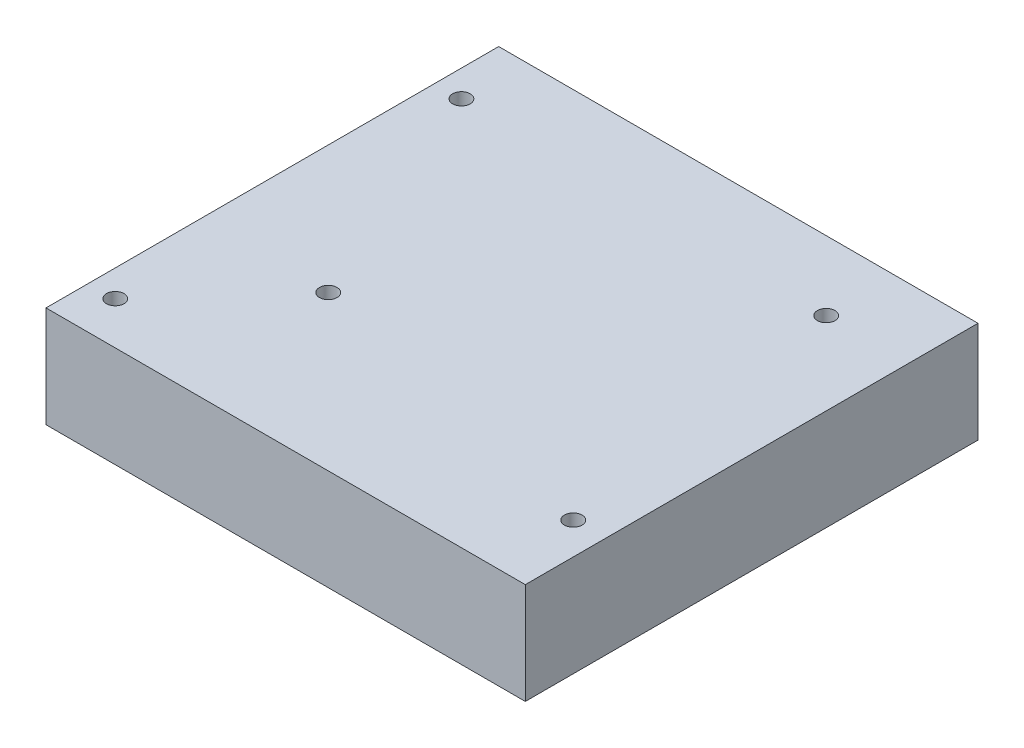
SolidWorks part; units mm, degrees
ref_plane "Front Plane" through (0, 0, 0) normal (0, 0, 1) x (1, 0, 0)
ref_plane "Top Plane" through (0, 0, 0) normal (0, 1, 0) x (1, 0, 0)
ref_plane "Right Plane" through (0, 0, 0) normal (1, 0, 0) x (0, 0, -1)
sketch "Sketch1" plane through (0, 0, 0) normal (0, 1, 0) x (1, 0, 0)
  line L1 (0, 0) -> (90, 0)
  line L2 (0, 0) -> (0, 85)
  line L3 (0, 85) -> (90, 85)
  line L4 (90, 0) -> (90, 85)
  circle A0 centre (5, 73) radius 1.65
  circle A1 centre (5, 8) radius 1.65
  circle A2 centre (84, 15) radius 1.65
  circle A3 centre (24, 29) radius 1.65
  circle A4 centre (74.5, 72) radius 1.65
  point P7 (5, 8)
  point P8 (24, 29)
  point P9 (84, 15)
  point P10 (74.5, 72)
  dimension "D13" = 3.3
  dimension "D14" = 3.3
  dimension "D15" = 3.3
  dimension "D16" = 3.3
  dimension "D17" = 3.3
  dimension "D1" = 90
  dimension "D2" = 85
  dimension "D3" = 5
  dimension "D4" = 8
  dimension "D5" = 5
  dimension "D6" = 12
  dimension "D7" = 24
  dimension "D8" = 29
  dimension "D9" = 15.5
  dimension "D10" = 13
  dimension "D11" = 6
  dimension "D12" = 15
extrude "Boss-Extrude1" add sketch "Sketch1" along normal blind 19
sketch "Sketch2" plane through (0, 19, 0) normal (0, 1, 0) x (1, 0, 0)
  line L0 (0, 42.5) -> (90, 42.5) construction
  line L1 (0, 85) -> (0, 0) construction
  line L2 (90, 0) -> (90, 85) construction
  point P6 (45, 42.5)
sketch "Sketch4" plane through (0, 0, 0) normal (0, -1, 0) x (1, 0, 0)
  line L0 (0, -85) -> (0, 0) construction
  line L1 (0, 0) -> (90, 0) construction
  circle A0 centre (30, -4) radius 10
  circle A1 centre (13, -30) radius 10
  dimension "D5" = 20
  dimension "D6" = 20
  dimension "D1" = 13
  dimension "D2" = 30
  dimension "D3" = 4
  dimension "D4" = 30
equation "\"rad\"=0.33"
equation "\"D13@Sketch1\"=\"rad\""
equation "\"D14@Sketch1\"=\"rad\""
equation "\"D15@Sketch1\"=\"rad\""
equation "\"D16@Sketch1\"=\"rad\""
equation "\"D17@Sketch1\"=\"rad\""
